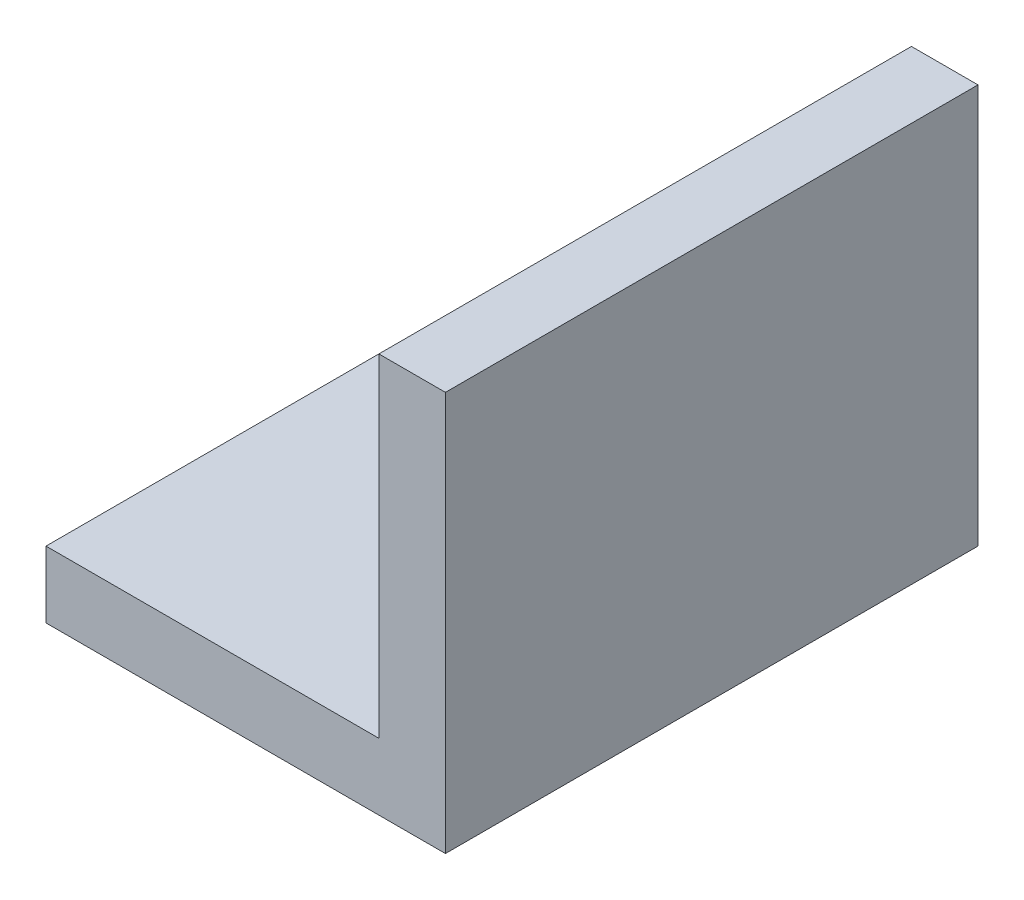
SolidWorks part; units mm, degrees
ref_plane "Front Plane" through (0, 0, 0) normal (0, 0, 1) x (1, 0, 0)
ref_plane "Top Plane" through (0, 0, 0) normal (0, 1, 0) x (1, 0, 0)
ref_plane "Right Plane" through (0, 0, 0) normal (1, 0, 0) x (0, 0, -1)
sketch "Sketch1" plane through (0, 0, 0) normal (0, 0, 1) x (1, 0, 0)
  line L0 (0, 0) -> (19.05, 0)
  line L1 (19.05, 0) -> (19.05, 19.05)
  line L2 (19.05, 19.05) -> (15.875, 19.05)
  line L3 (0, 0) -> (0, 3.175)
  line L4 (0, 3.175) -> (15.875, 3.175)
  line L5 (15.875, 3.175) -> (15.875, 19.05)
extrude "Boss-Extrude1" add sketch "Sketch1" along normal blind 25.4
